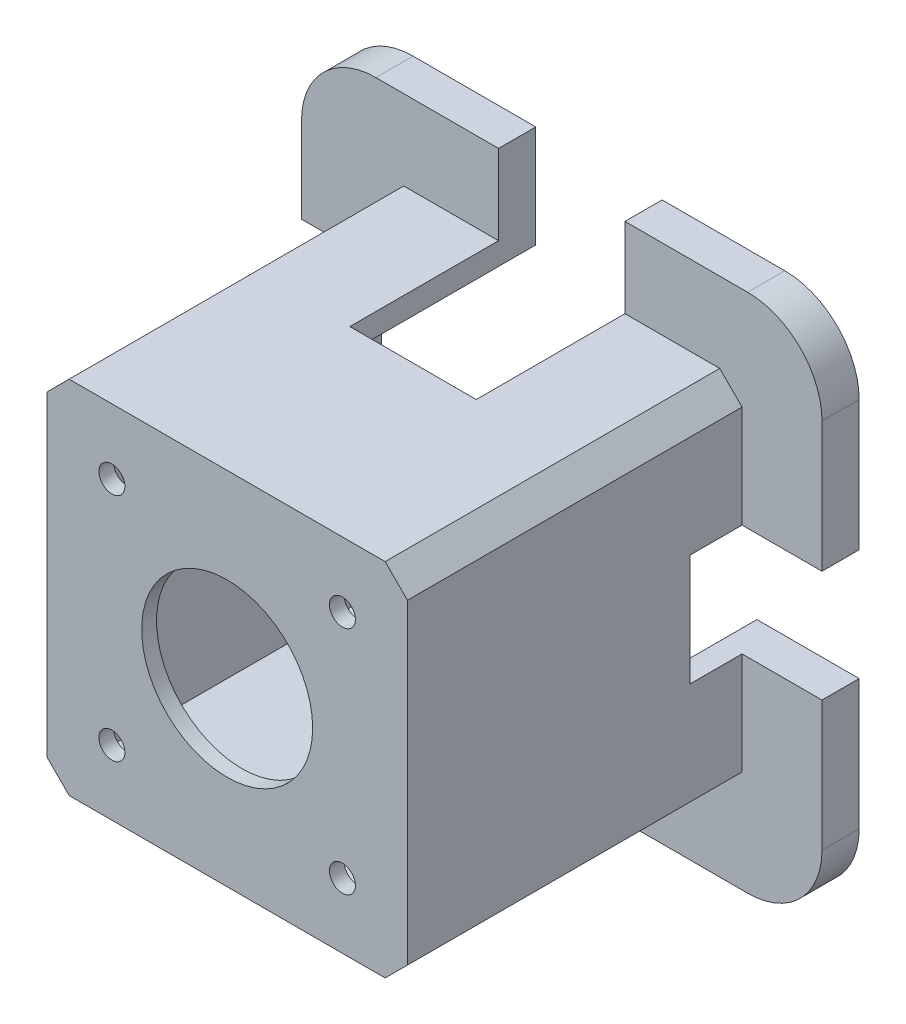
SolidWorks part; units mm, degrees
ref_plane "前视基准面" through (0, 0, 0) normal (0, 0, 1) x (1, 0, 0)
ref_plane "上视基准面" through (0, 0, 0) normal (0, 1, 0) x (1, 0, 0)
ref_plane "右视基准面" through (0, 0, 0) normal (1, 0, 0) x (0, 0, -1)
sketch "草图1" plane through (0, 0, 0) normal (0, 0, 1) x (1, 0, 0)
  line L1 (21.25, -21.25) -> (-21.25, -21.25)
  line L2 (21.25, -21.25) -> (21.25, 21.25)
  line L3 (21.25, 21.25) -> (-21.25, 21.25)
  line L4 (-21.25, -21.25) -> (-21.25, 21.25)
  line L5 (0, 21.25) -> (0, -21.25) construction
  line L6 (21.25, 0) -> (-21.25, 0) construction
  circle A0 centre (15.5, 15.5) radius 1.75
  circle A1 centre (15.5, -15.5) radius 1.75
  circle A2 centre (-15.5, -15.5) radius 1.75
  circle A3 centre (-15.5, 15.5) radius 1.75
  point P0 (0, 0)
  point P18 (0, 0)
  dimension "D3" = 3.5
  dimension "D4" = 31
  dimension "D5" = 31
  dimension "D1" = 42.5
  dimension "D2" = 42.5
  dimension "D6" = 4
extrude "凸台-拉伸1" add sketch "草图1" along normal blind 2
sketch "草图2" plane through (0, 0, 2) normal (0, 0, 1) x (1, 0, 0)
  line L1 (21.25, -21.25) -> (-21.25, -21.25)
  line L2 (21.25, -21.25) -> (21.25, 21.25)
  line L3 (21.25, 21.25) -> (-21.25, 21.25)
  line L4 (-21.25, -21.25) -> (-21.25, 21.25)
  line L5 (0, 21.25) -> (0, -21.25) construction
  line L6 (21.25, 0) -> (-21.25, 0) construction
  point P0 (0, 0)
extrude "拉伸-薄壁2" add sketch "草图2" against normal blind 50 thin thin type one direction wall 3
chamfer "倒角1" distance 3 angle 45 4 edges at (24.25, 24.25, -23) (24.25, -24.25, -23) (-24.25, -24.25, -23) (-24.25, 24.25, -23)
sketch "草图3" plane through (0, 0, -48) normal (0, 0, -1) x (-1, 0, 0)
  line L5 (0, 24.25) -> (0, -24.25) construction
  line L6 (24.25, 0) -> (-24.25, 0) construction
  line L7 (35, -35) -> (-35, -35)
  line L8 (35, -35) -> (35, 35)
  line L9 (35, 35) -> (-35, 35)
  line L10 (-35, -35) -> (-35, 35)
  line L11 (0, 35) -> (0, -35) construction
  line L12 (35, 0) -> (-35, 0) construction
  line L15 (21.25, -21.25) -> (-21.25, -21.25)
  line L16 (21.25, -21.25) -> (21.25, 21.25)
  line L17 (21.25, 21.25) -> (-21.25, 21.25)
  line L18 (-21.25, -21.25) -> (-21.25, 21.25)
  line L19 (0, 21.25) -> (0, -21.25) construction
  line L20 (21.25, 0) -> (-21.25, 0) construction
  point P0 (0, 0)
  point P1 (0, 0)
  point P4 (0, 0)
  dimension "D1" = 70
  dimension "D2" = 70
extrude "凸台-拉伸2" add sketch "草图3" against normal blind 5
fillet "圆角1" radius 10 4 edges at (35, 35, -45.5) (35, -35, -45.5) (-35, -35, -45.5) (-35, 35, -45.5)
sketch "草图5" plane through (0, 35, 0) normal (0, 1, 0) x (1, 0, 0)
  line L1 (8.5, 23) -> (-8.5, 23)
  line L2 (8.5, 23) -> (8.5, 56.2253)
  line L3 (8.5, 56.2253) -> (-8.5, 56.2253)
  line L4 (-8.5, 23) -> (-8.5, 56.2253)
  line L5 (0, 56.2253) -> (0, 23) construction
  line L6 (8.5, 39.6126) -> (-8.5, 39.6126) construction
  line L7 (-25, 48) -> (25, 48) construction
  point P0 (0, 39.6126)
  dimension "D1" = 17
  dimension "D2" = 25
extrude "切除-拉伸2" cut sketch "草图5" against normal up to surface (13.75 mm away) up to face at (0, 21.25, -24)
sketch "草图6" plane through (-35, 0, 0) normal (-1, 0, 0) x (0, 0, 1)
  line L0 (-48, -25) -> (-48, 25) construction
  line L1 (-40, -13.5) -> (-57.0324, -13.5)
  line L2 (-40, -13.5) -> (-40, 13.5)
  line L3 (-40, 13.5) -> (-57.0324, 13.5)
  line L4 (-57.0324, -13.5) -> (-57.0324, 13.5)
  line L5 (-48.5162, 13.5) -> (-48.5162, -13.5) construction
  line L6 (-40, 0) -> (-57.0324, 0) construction
  point P0 (-48.5162, 0)
  dimension "D1" = 27
  dimension "D2" = 8
extrude "切除-拉伸3" cut sketch "草图6" against normal up to surface (13.75 mm away) up to face at (-21.25, 0, -24)
sketch "草图7" plane through (0, 0, 2) normal (0, 0, 1) x (1, 0, 0)
  circle A0 centre (0, 0) radius 11.5
  dimension "D1" = 23
extrude "切除-拉伸4" cut sketch "草图7" against normal blind 10
sketch "草图9" plane through (0, -35, 0) normal (0, -1, 0) x (1, 0, 0)
  line L0 (0, 0) -> (0, -63.2985) construction
  line L1 (25, -43) -> (-25, -43) construction
  line L2 (7.5, -50) -> (-7.5, -50)
  line L3 (7.5, -50) -> (7.5, -36)
  line L4 (7.5, -36) -> (-7.5, -36)
  line L5 (-7.5, -50) -> (-7.5, -36)
  line L6 (0, -36) -> (0, -50) construction
  line L7 (7.5, -43) -> (-7.5, -43) construction
  line L8 (25, -48) -> (-25, -48) construction
  point P3 (0, -43)
  dimension "D1" = 15
  dimension "D2" = 12
extrude "切除-拉伸5" cut sketch "草图9" against normal up to next
sketch "草图10" plane through (35, 0, 0) normal (1, 0, 0) x (0, 0, -1)
  line L0 (0, 0) -> (74.1497, 0) construction
  line L1 (48, 25) -> (48, -25) construction
  line L2 (55.7222, -7.5) -> (36, -7.5)
  line L3 (55.7222, -7.5) -> (55.7222, 7.5)
  line L4 (55.7222, 7.5) -> (36, 7.5)
  line L5 (36, -7.5) -> (36, 7.5)
  line L6 (45.8611, 7.5) -> (45.8611, -7.5) construction
  line L7 (55.7222, 0) -> (36, 0) construction
  point P3 (45.8611, 0)
  dimension "D1" = 15
  dimension "D2" = 12
extrude "切除-拉伸6" cut sketch "草图10" against normal up to next
